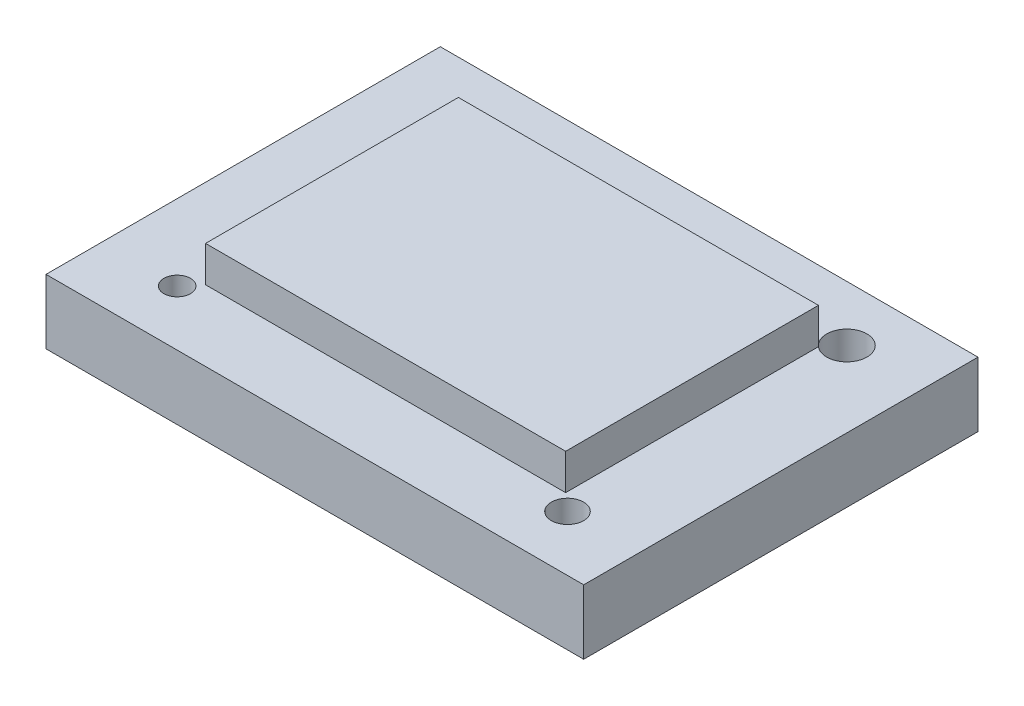
SolidWorks part; units mm, degrees
ref_plane "前视基准面" through (0, 0, 0) normal (0, 0, 1) x (1, 0, 0)
ref_plane "上视基准面" through (0, 0, 0) normal (0, 1, 0) x (1, 0, 0)
ref_plane "右视基准面" through (0, 0, 0) normal (1, 0, 0) x (0, 0, -1)
other "Configuration Table"
sketch "01_Base_Profile" plane through (0, 0, 0) normal (0, 1, 0) x (1, 0, 0)
  line L1 (-75, -55) -> (75, -55)
  line L2 (-75, -55) -> (-75, 55)
  line L3 (-75, 55) -> (75, 55)
  line L4 (75, -55) -> (75, 55)
  line L5 (-75, -55) -> (75, 55) construction
  line L6 (-75, 55) -> (75, -55) construction
  line L7 (-35, -12) -> (35, -12)
  line L8 (-35, -12) -> (-35, 12)
  line L9 (-35, 12) -> (35, 12)
  line L10 (35, -12) -> (35, 12)
  line L11 (-35, -12) -> (35, 12) construction
  line L12 (-35, 12) -> (35, -12) construction
  circle A0 centre (-53.8873, -39.5173) radius 3.7116
  circle A1 centre (55, -39.5173) radius 4.5
  circle A2 centre (-53.8873, 38) radius 1.2236
  circle A3 centre (53.8873, 39.5173) radius 5.6127
  point P0 (0, 0)
  point P14 (0, 0)
extrude "01_Base_Extrude" add sketch "01_Base_Profile" along normal blind 18
sketch "02_Boss_Profile" plane through (0, 0, 0) normal (0, 1, 0) x (1, 0, 0)
  line L1 (-50.2263, -35.263) -> (50.2263, -35.263)
  line L2 (-50.2263, -35.263) -> (-50.2263, 35.263)
  line L3 (-50.2263, 35.263) -> (50.2263, 35.263)
  line L4 (50.2263, -35.263) -> (50.2263, 35.263)
  line L5 (-50.2263, -35.263) -> (50.2263, 35.263) construction
  line L6 (-50.2263, 35.263) -> (50.2263, -35.263) construction
  circle A0 centre (53.8873, 39.5173) radius 5.6127 construction
  point P0 (0, 0)
extrude "02_Reinforcement_Boss" add sketch "02_Boss_Profile" along normal blind 28
